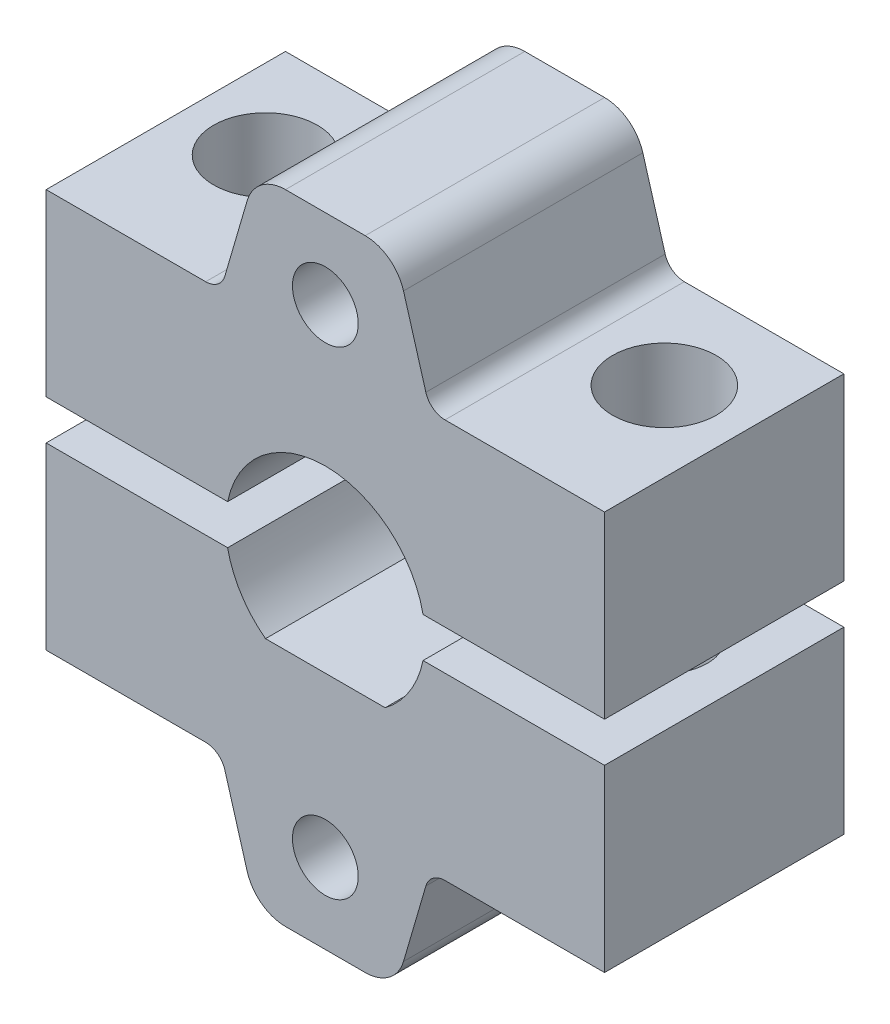
SolidWorks part; units mm, degrees
material "6061 合金"
ref_plane "前视基准面" through (0, 0, 0) normal (0, 0, 1) x (1, 0, 0)
ref_plane "上视基准面" through (0, 0, 0) normal (0, 1, 0) x (1, 0, 0)
ref_plane "右视基准面" through (0, 0, 0) normal (1, 0, 0) x (0, 0, -1)
sketch "草图1" plane through (0, 0, 0) normal (0, 0, 1) x (1, 0, 0)
  line L0 (-3, -4) -> (3, -4)
  line L8 (0, 0) -> (0, -14.8013) construction
  line L13 (-12, 0) -> (12, 0) construction
  line L18 (-3.92, 14.56) -> (-5.04, 10.72)
  line L19 (-6, 10) -> (-14, 10)
  line L20 (0, 16) -> (0, 0) construction
  line L23 (-4.899, 1) -> (-14, 1)
  line L24 (-14, 1) -> (-14, 10)
  line L34 (2, 16) -> (-2, 16)
  line L36 (3.92, 14.56) -> (5.04, 10.72)
  line L37 (6, 10) -> (14, 10)
  line L38 (4.899, 1) -> (14, 1)
  line L39 (14, 1) -> (14, 10)
  line L40 (4.899, -1) -> (14, -1)
  line L41 (14, -1) -> (14, -10)
  line L42 (6, -10) -> (14, -10)
  line L43 (3.92, -14.56) -> (5.04, -10.72)
  line L44 (2, -16) -> (-2, -16)
  line L45 (-3.92, -14.56) -> (-5.04, -10.72)
  line L46 (-6, -10) -> (-14, -10)
  line L47 (-14, -1) -> (-14, -10)
  line L48 (-4.899, -1) -> (-14, -1)
  arc A0 (3, -4) -> (4.899, -1) centre (0, 0) ccw
  circle A1 centre (0, 0) radius 12 construction
  arc A16 (4.899, 1) -> (-4.899, 1) centre (0, 0) ccw
  arc A20 (-3, -4) -> (-4.899, -1) centre (0, 0) cw
  circle A22 centre (0, 12) radius 1.65
  circle A23 centre (0, -12) radius 1.65
  circle A24 centre (0, 0) radius 16 construction
  arc A25 (-5.04, 10.72) -> (-6, 10) centre (-6, 11) cw
  arc A26 (-3.92, 14.56) -> (-2, 16) centre (-2, 14) cw
  arc A27 (3.92, 14.56) -> (2, 16) centre (2, 14) ccw
  arc A28 (5.04, 10.72) -> (6, 10) centre (6, 11) ccw
  arc A29 (5.04, -10.72) -> (6, -10) centre (6, -11) cw
  arc A30 (3.92, -14.56) -> (2, -16) centre (2, -14) cw
  arc A31 (-3.92, -14.56) -> (-2, -16) centre (-2, -14) ccw
  arc A32 (-5.04, -10.72) -> (-6, -10) centre (-6, -11) ccw
  point P19 (0, 0)
  point P26 (0, -4)
  point P44 (-5, 10)
  point P47 (-4, 16)
  dimension "D1" = 10
  dimension "D3" = 24
  dimension "D5" = 16
  dimension "D6" = 1
  dimension "D7" = 14
  dimension "D4" = 3.3
  dimension "D9" = 32
  dimension "D8" = 1
  dimension "D13" = 2
  dimension "D2" = 4
  dimension "D10" = 4
  dimension "D11" = 10
  dimension "D12" = 9
  dimension "D14" = 8
  dimension "D15" = 2
extrude "凸台-拉伸1" add sketch "草图1" along normal blind 12
cosmetic thread "装饰螺纹线7" parameters "D2"=4
cosmetic thread "装饰螺纹线8" parameters "D2"=4
sketch "草图3" plane through (0, 10, 0) normal (0, 1, 0) x (1, 0, 0)
  line L0 (10, -5) -> (-10, -5) construction
  line L1 (0, -10) -> (0, -5) construction
  line L3 (0, -5) -> (0, 0) construction
  line L5 (14, 0) -> (6, 0) construction
  circle A0 centre (10, -5) radius 2.6
  circle A1 centre (-10, -5) radius 2.6
  dimension "D1" = 5.2
  dimension "D2" = 20
  dimension "D3" = 5
extrude "切除-拉伸2" cut sketch "草图3" against normal up to next (9 mm away) and the other way through all
sketch "草图4" plane through (0, -10, 0) normal (0, 1, 0) x (1, 0, 0)
  circle A0 centre (10, -5) radius 2.15
  circle A1 centre (-10, -5) radius 2.15
  dimension "D1" = 4.3
extrude "切除-拉伸3" cut sketch "草图4" along normal through all
cosmetic thread "装饰螺纹线5" parameters "D2"=5
cosmetic thread "装饰螺纹线6" parameters "D2"=5
